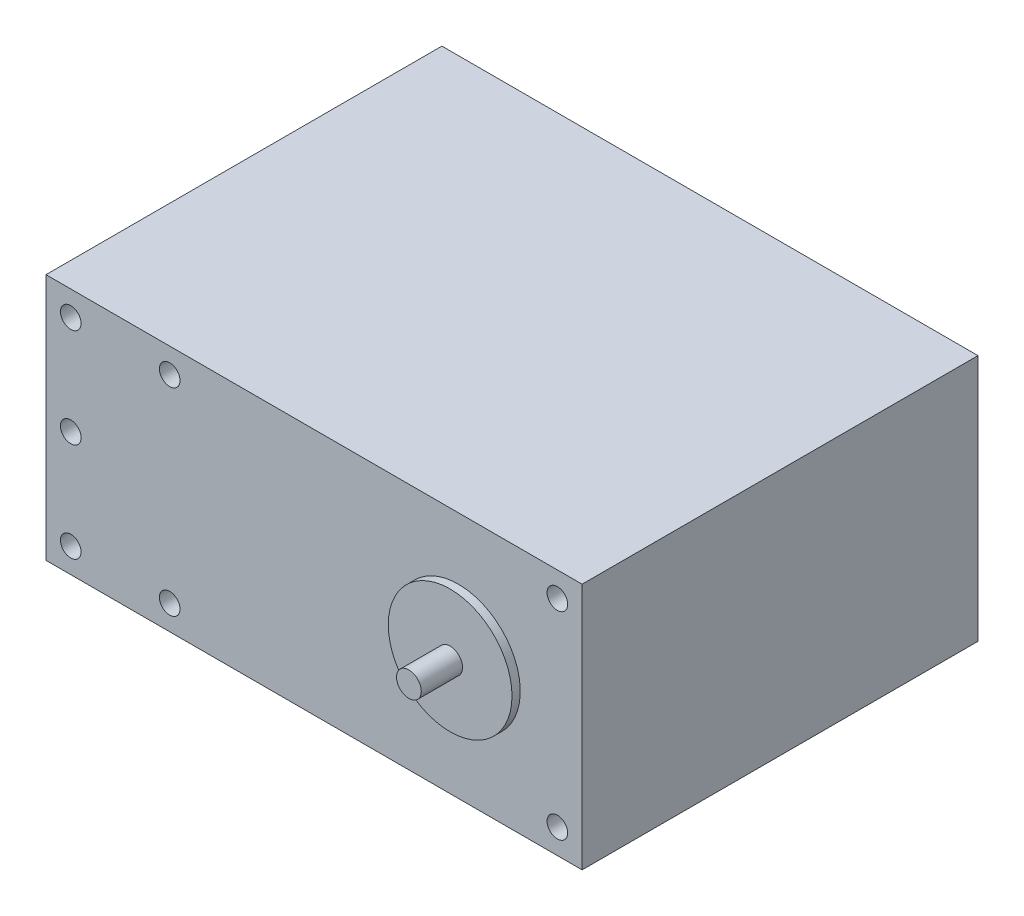
SolidWorks part; units mm, degrees
ref_plane "正面" through (0, 0, 0) normal (0, 0, 1) x (1, 0, 0)
ref_plane "平面" through (0, 0, 0) normal (0, 1, 0) x (1, 0, 0)
ref_plane "右側面" through (0, 0, 0) normal (1, 0, 0) x (0, 0, -1)
sketch "ｽｹｯﾁ1" plane through (0, 0, 0) normal (0, 0, 1) x (1, 0, 0)
  line L1 (0, 0) -> (65, 0)
  line L2 (0, 0) -> (0, 30)
  line L3 (0, 30) -> (65, 30)
  line L4 (65, 0) -> (65, 30)
  dimension "D1" = 65
  dimension "D2" = 30
extrude "ﾎﾞｽ - 押し出し1" add sketch "ｽｹｯﾁ1" along normal blind 48
sketch "ｽｹｯﾁ2" plane through (0, 0, 48) normal (0, 0, 1) x (1, 0, 0)
  line L0 (0, 30) -> (0, 0) construction
  line L1 (65, 30) -> (0, 30) construction
  line L2 (0, 0) -> (65, 0) construction
  line L3 (65, 0) -> (65, 30) construction
  circle A0 centre (3, 27) radius 1.25
  circle A1 centre (15, 27) radius 1.25
  circle A2 centre (3, 3) radius 1.25
  circle A3 centre (3, 15) radius 1.25
  circle A4 centre (15, 3) radius 1.25
  circle A5 centre (62, 27) radius 1.25
  circle A6 centre (62, 3) radius 1.25
  dimension "D1" = 2.5
  dimension "D2" = 3
  dimension "D3" = 3
  dimension "D4" = 12
  dimension "D5" = 3
  dimension "D6" = 12
  dimension "D7" = 3
extrude "ｶｯﾄ - 押し出し1" cut sketch "ｽｹｯﾁ2" against normal blind 3
sketch "ｽｹｯﾁ3" plane through (0, 0, 48) normal (0, 0, 1) x (1, 0, 0)
  line L0 (65, 0) -> (65, 30) construction
  circle A0 centre (50, 15) radius 7.5
  circle A1 centre (50, 15) radius 1.5
  dimension "D1" = 15
  dimension "D2" = 15
  dimension "D3" = 3
extrude "ﾎﾞｽ - 押し出し2" add sketch "ｽｹｯﾁ3" along normal blind 1
sketch "ｽｹｯﾁ4" plane through (0, 0, 48) normal (0, 0, 1) x (1, 0, 0)
  circle A0 centre (50, 15) radius 1.5
extrude "ﾎﾞｽ - 押し出し3" add sketch "ｽｹｯﾁ4" along normal blind 6
sketch "ｽｹｯﾁ5" plane through (0, 0, 0) normal (0, 0, -1) x (-1, 0, 0)
  line L0 (0, 30) -> (0, 0) construction
  line L1 (0, 0) -> (-65, 0) construction
  line L2 (-65, 30) -> (0, 30) construction
  line L3 (-65, 0) -> (-65, 30) construction
  circle A0 centre (-3, 3) radius 1.25
  circle A1 centre (-3, 27) radius 1.25
  circle A2 centre (-27, 27) radius 1.25
  circle A3 centre (-27, 3) radius 1.25
  circle A4 centre (-62, 27) radius 1.25
  circle A5 centre (-62, 3) radius 1.25
  dimension "D1" = 3
  dimension "D2" = 3
  dimension "D3" = 3
  dimension "D4" = 24
  dimension "D5" = 3
extrude "ｶｯﾄ - 押し出し2" cut sketch "ｽｹｯﾁ5" against normal blind 4
sketch "ｽｹｯﾁ6" plane through (0, 0, 0) normal (0, 0, -1) x (-1, 0, 0)
  line L0 (-65, 0) -> (-65, 30) construction
  circle A0 centre (-50, 15) radius 7.5
  circle A1 centre (-50, 15) radius 1.5
  dimension "D1" = 15
  dimension "D3" = 3
  dimension "D2" = 15
extrude "ﾎﾞｽ - 押し出し4" add sketch "ｽｹｯﾁ6" along normal blind 1
sketch "ｽｹｯﾁ7" plane through (0, 0, 0) normal (0, 0, -1) x (-1, 0, 0)
  circle A0 centre (-50, 15) radius 1.5
extrude "ﾎﾞｽ - 押し出し5" add sketch "ｽｹｯﾁ7" along normal blind 6
